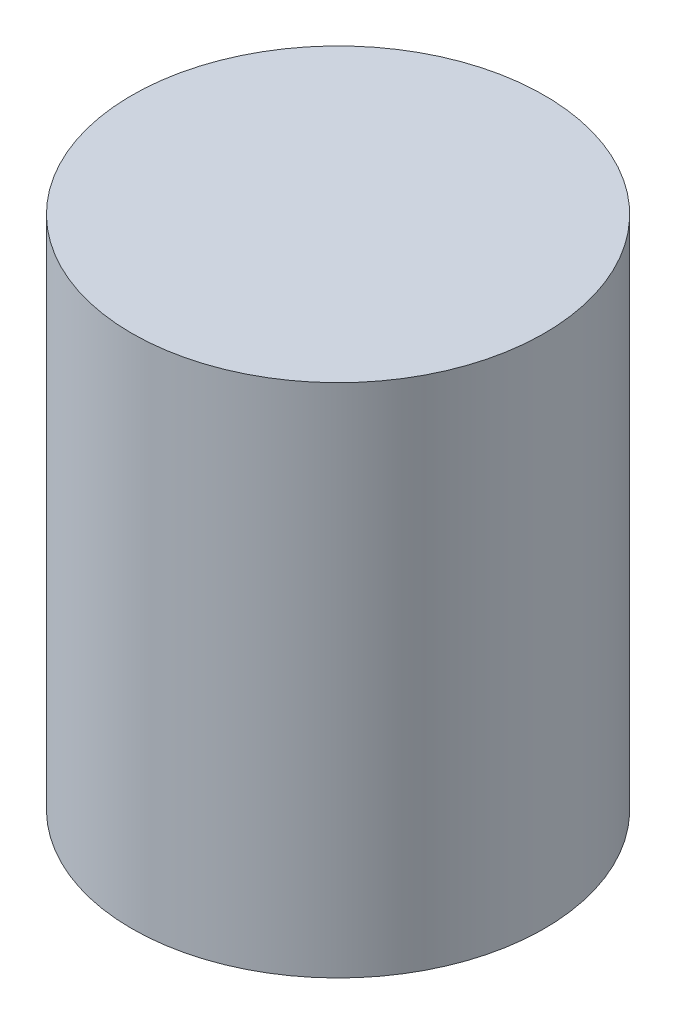
SolidWorks part; units mm, degrees
ref_plane "Front Plane" through (0, 0, 0) normal (0, 0, 1) x (1, 0, 0)
ref_plane "Top Plane" through (0, 0, 0) normal (0, 1, 0) x (1, 0, 0)
ref_plane "Right Plane" through (0, 0, 0) normal (1, 0, 0) x (0, 0, -1)
sketch "Sketch1" plane through (0, 0, 0) normal (0, 1, 0) x (1, 0, 0)
  circle A0 centre (0, 0) radius 2.4
  dimension "D1" = 4.8
extrude "Boss-Extrude1" add sketch "Sketch1" along normal blind 6
